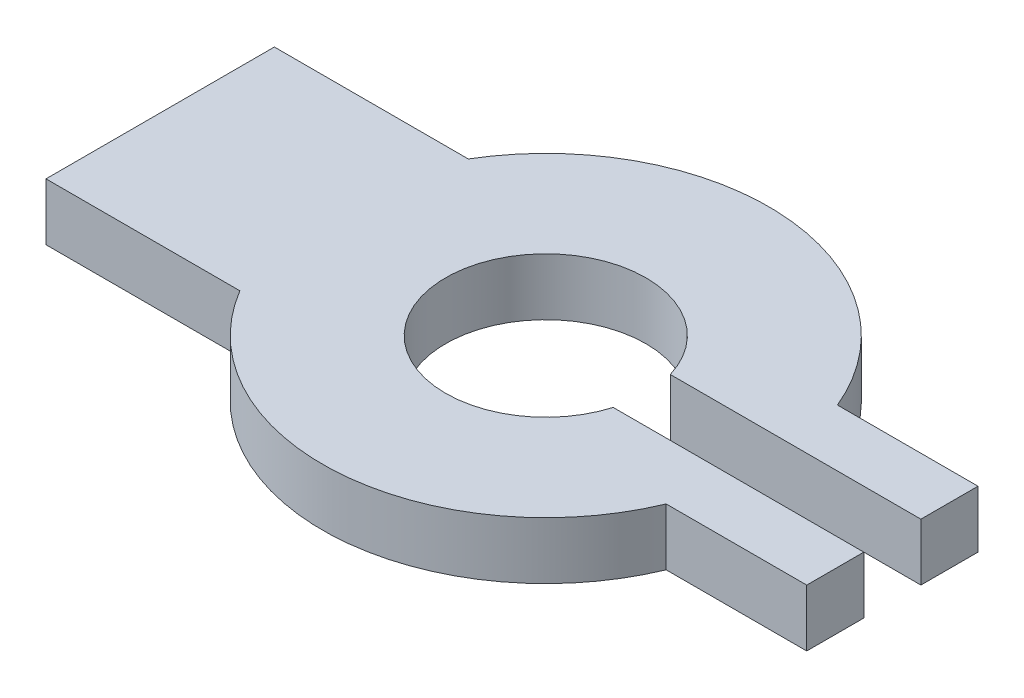
SolidWorks part; units mm, degrees
material "6061 Alloy"
ref_plane "Front Plane" through (0, 0, 0) normal (0, 0, 1) x (1, 0, 0)
ref_plane "Top Plane" through (0, 0, 0) normal (0, 1, 0) x (1, 0, 0)
ref_plane "Right Plane" through (0, 0, 0) normal (1, 0, 0) x (0, 0, -1)
sketch "Sketch1" plane through (0, 0, 0) normal (0, 1, 0) x (1, 0, 0)
  line L0 (-33.1379, 12.5768) -> (-39.4879, 12.5768)
  line L1 (-39.4879, 12.5768) -> (-39.4879, -12.8232)
  line L2 (-39.4879, -12.8232) -> (-33.1379, -12.8232)
  line L3 (14.0757, 3.0518) -> (41.9516, 3.0518)
  line L4 (14.0757, -3.2982) -> (41.9516, -3.2982)
  line L5 (-33.1379, 12.5768) -> (-17.922, 12.5768)
  line L6 (-33.1379, -12.8232) -> (-17.922, -12.8232)
  line L7 (41.9516, 3.0518) -> (41.9516, 9.4018)
  line L8 (41.9516, 9.4018) -> (26.317, 9.4018)
  line L9 (41.9516, -3.2982) -> (41.9516, -9.6482)
  line L10 (41.9516, -9.6482) -> (26.317, -9.6482)
  arc A0 (14.0757, 3.0518) -> (14.0757, -3.2982) centre (3.4, -0.1232) ccw
  arc A1 (-17.922, -12.8232) -> (26.317, -9.6482) centre (3.4, -0.1232) ccw
  arc A2 (26.317, 9.4018) -> (-17.922, 12.5768) centre (3.4, -0.1232) ccw
extrude "Boss-Extrude1" add sketch "Sketch1" along normal blind 6.35
